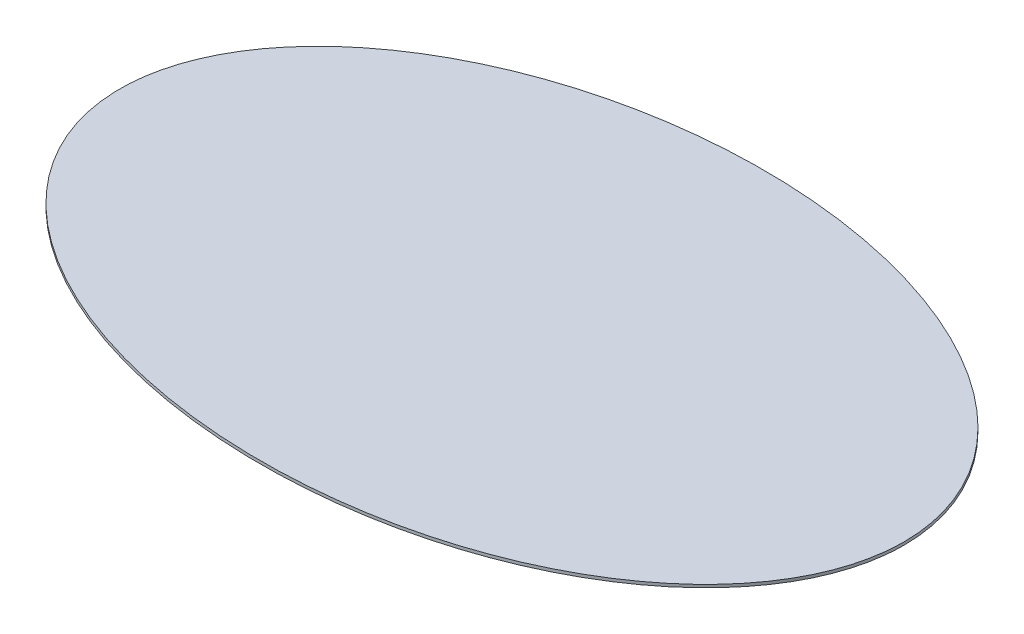
SolidWorks part; units mm, degrees
ref_plane "Front" through (0, 0, 0) normal (0, 0, 1) x (1, 0, 0)
ref_plane "Top" through (0, 0, 0) normal (0, 1, 0) x (1, 0, 0)
ref_plane "Right" through (0, 0, 0) normal (1, 0, 0) x (0, 0, -1)
sketch "Esquisse1" plane through (0, 0, 0) normal (0, 1, 0) x (1, 0, 0)
  ellipse E0 centre (0, 0) end of major axis (6.7, 0) minor radius 4.3
  dimension "D1" = 13.4
  dimension "D2" = 8.6
extrude "Boss.-Extru.1" add sketch "Esquisse1" along normal blind 0.05
